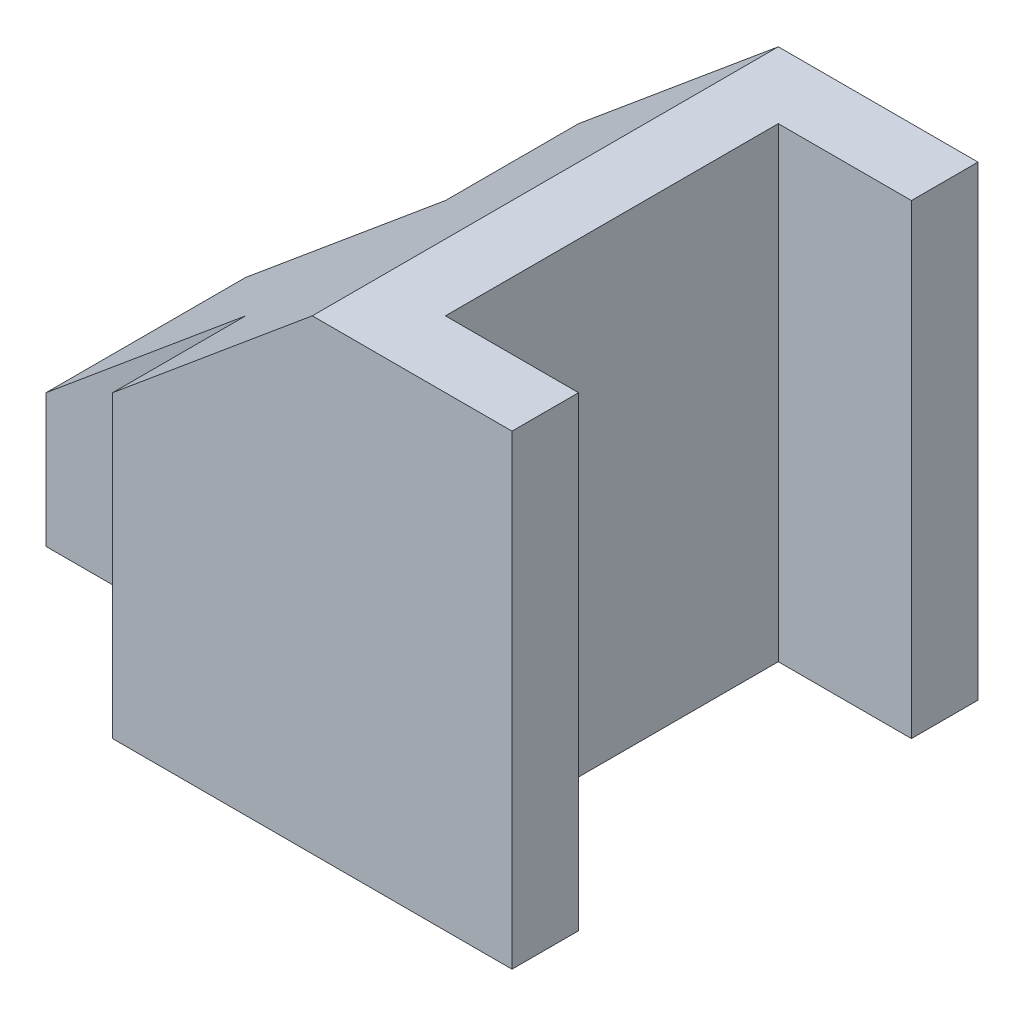
SolidWorks part; units mm, degrees
ref_plane "Front Plane" through (0, 0, 0) normal (0, 0, 1) x (1, 0, 0)
ref_plane "Top Plane" through (0, 0, 0) normal (0, 1, 0) x (1, 0, 0)
ref_plane "Right Plane" through (0, 0, 0) normal (1, 0, 0) x (0, 0, -1)
sketch "Sketch1" plane through (0, 0, 0) normal (0, 0, 1) x (1, 0, 0)
  line L0 (0, 0) -> (45000, 0)
  line L1 (45000, 0) -> (45000, 35000)
  line L2 (45000, 35000) -> (30000, 35000)
  line L3 (30000, 35000) -> (0, 10000)
  line L4 (0, 10000) -> (0, 0)
  dimension "D1" = 10000
  dimension "D2" = 45000
  dimension "D3" = 35000
  dimension "D4" = 15000
extrude "Boss-Extrude1" add sketch "Sketch1" against normal blind 35000
sketch "Sketch3" plane through (0, 35000, 0) normal (0, 1, 0) x (1, 0, 0)
  line L0 (25628.6314, 17500) -> (54333.825, 17500) construction
  line L1 (45000, 35000) -> (45000, 0) construction
  line L2 (45000, 30000) -> (35000, 30000)
  line L3 (45000, 30000) -> (45000, 5000)
  line L4 (45000, 5000) -> (35000, 5000)
  line L5 (35000, 30000) -> (35000, 5000)
  dimension "D1" = 12500
  dimension "D2" = 25000
  dimension "D3" = 10000
extrude "Cut-Extrude1" cut sketch "Sketch3" against normal through all
sketch "Sketch4" plane through (0, 0, 0) normal (0, 0, 1) x (1, 0, 0)
  line L0 (0, 0) -> (15000, 0)
  line L1 (0, 0) -> (45000, 0) construction
  line L2 (15000, 0) -> (15000, 22500)
  line L3 (30000, 35000) -> (0, 10000) construction
  line L4 (15000, 22500) -> (0, 10000)
  line L5 (0, 10000) -> (0, 0)
  dimension "D1" = 15000
extrude "Cut-Extrude2" cut sketch "Sketch4" against normal blind 10000
sketch "Sketch5" plane through (0, 0, -35000) normal (0, 0, -1) x (-1, 0, 0)
  line L0 (0, 10000) -> (-15000, 22500)
  line L1 (-30000, 35000) -> (0, 10000) construction
  line L2 (-15000, 22500) -> (-15000, 0)
  line L3 (0, 0) -> (-45000, 0) construction
  line L4 (-15000, 0) -> (0, 0)
  line L5 (0, 0) -> (0, 10000)
  dimension "D1" = 15000
extrude "Cut-Extrude3" cut sketch "Sketch5" against normal blind 10000
